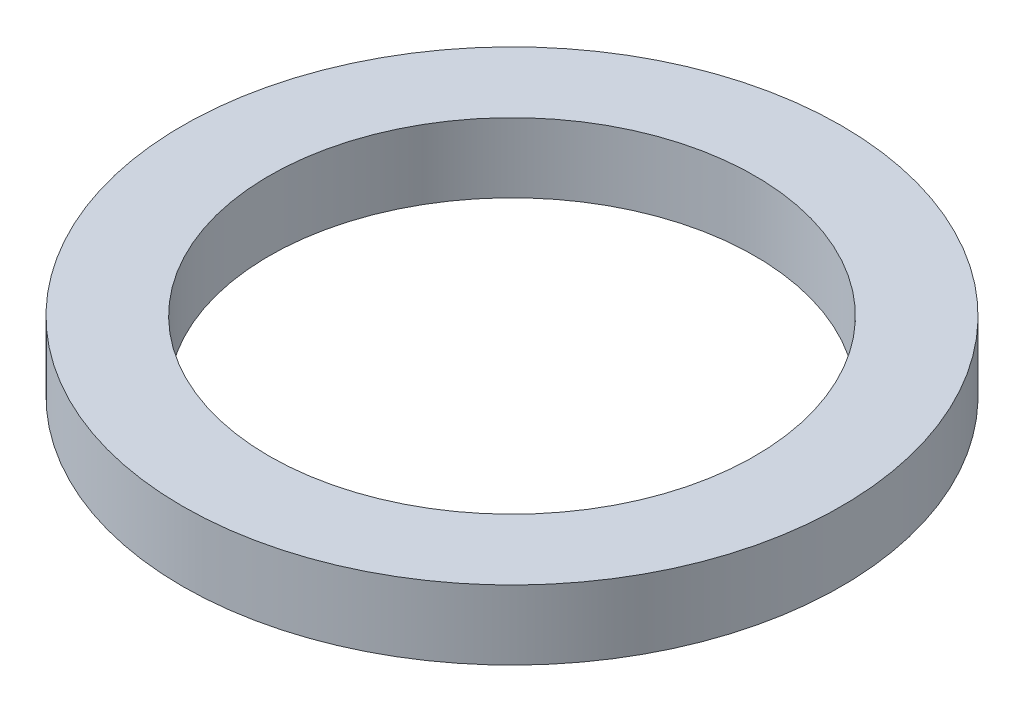
SolidWorks part; units mm, degrees
ref_plane "前基準面" through (0, 0, 0) normal (0, 0, 1) x (1, 0, 0)
ref_plane "上基準面" through (0, 0, 0) normal (0, 1, 0) x (1, 0, 0)
ref_plane "右基準面" through (0, 0, 0) normal (1, 0, 0) x (0, 0, -1)
sketch "草圖1" plane through (0, 0, 0) normal (0, 1, 0) x (1, 0, 0)
  circle A0 centre (0, 0) radius 35
  circle A1 centre (0, 0) radius 47.5
  dimension "D1" = 70
  dimension "D2" = 95
extrude "填料-伸長1" add sketch "草圖1" along normal blind 10
